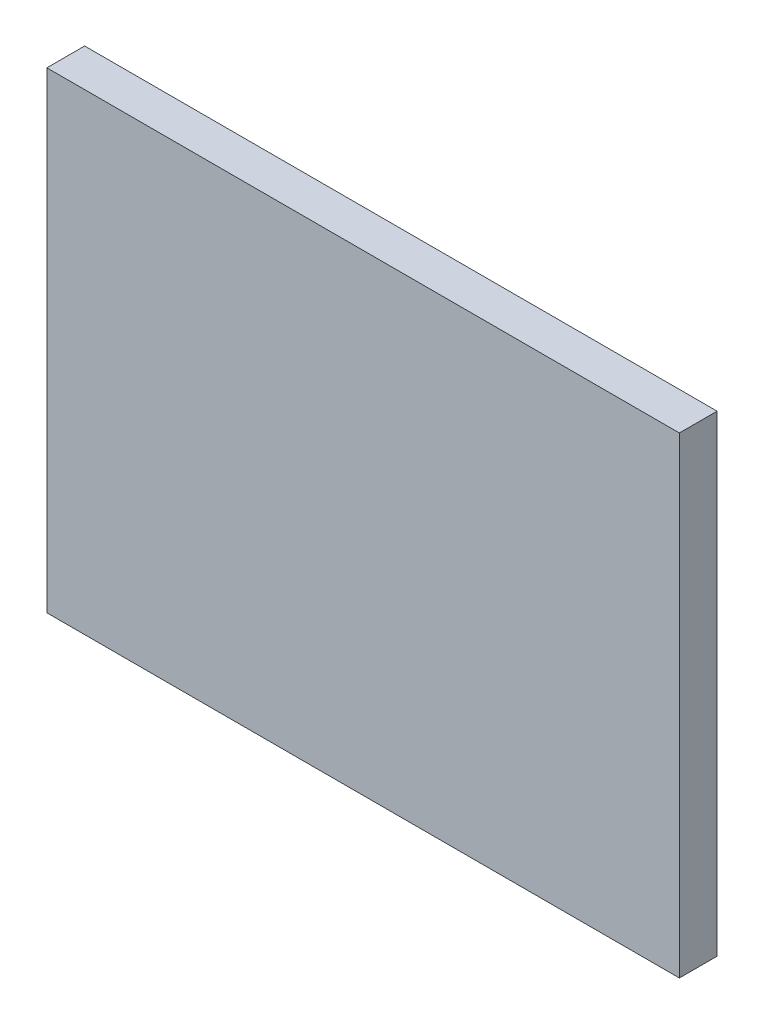
SolidWorks part; units mm, degrees
material "Pine"
ref_plane "Front Plane" through (0, 0, 0) normal (0, 0, 1) x (1, 0, 0)
ref_plane "Top Plane" through (0, 0, 0) normal (0, 1, 0) x (1, 0, 0)
ref_plane "Right Plane" through (0, 0, 0) normal (1, 0, 0) x (0, 0, -1)
sketch "Sketch1" plane through (0, 0, 0) normal (0, 0, 1) x (1, 0, 0)
  line L0 (-5300.6625, 1520.825) -> (-5451.475, 1520.825)
  line L1 (-5456.2375, 1384.3) -> (-5456.2375, 1516.0625)
  line L2 (-5557.8375, 1546.225) -> (-5194.3, 1546.225)
  line L3 (-5557.8375, 1539.875) -> (-5194.3, 1539.875)
  line L4 (-5297.4875, 1377.95) -> (-5454.65, 1377.95)
  line L5 (-5291.1375, 1384.3) -> (-5291.1375, 1516.0625)
  line L6 (-5300.6625, 1525.5875) -> (-5451.475, 1525.5875)
  line L7 (-5461, 1384.3) -> (-5461, 1516.0625)
  line L8 (-5297.4875, 1382.7125) -> (-5454.65, 1382.7125)
  line L9 (-5295.9, 1384.3) -> (-5295.9, 1516.0625)
  line L10 (-5740.4, 998.5375) -> (-5740.4, 1181.1)
  line L11 (-5740.4, 1181.1) -> (-5512.5938, 1181.1)
  line L12 (-5512.5938, 1181.1) -> (-5512.5938, 998.5375)
  line L13 (-5512.5938, 998.5375) -> (-5740.4, 998.5375)
  line L14 (-5258.5938, 1181.1) -> (-5486.4, 1181.1)
  line L15 (-5258.5938, 998.5375) -> (-5258.5938, 1181.1)
  line L16 (-5486.4, 998.5375) -> (-5258.5938, 998.5375)
  line L17 (-5486.4, 1181.1) -> (-5486.4, 998.5375)
  line L18 (-5740.4, 898.525) -> (-5011.7375, 898.525)
  line L19 (-5168.1062, 1384.3) -> (-5168.1062, 1392.2375)
  line L20 (-5176.0437, 1400.175) -> (-5245.8937, 1400.175)
  line L21 (-5253.8313, 1392.2375) -> (-5253.8313, 1384.3)
  line L22 (-5451.475, 1512.8875) -> (-5451.475, 1384.3)
  line L23 (-5303.8375, 1516.0625) -> (-5448.3, 1516.0625)
  line L24 (-5498.3062, 1384.3) -> (-5451.475, 1384.3)
  line L25 (-5253.8313, 1384.3) -> (-5300.6625, 1384.3)
  line L26 (-5584.0312, 1384.3) -> (-5740.4, 1384.3)
  line L27 (-5564.1875, 1536.7) -> (-5740.4, 1536.7)
  line L28 (-5740.4, 1357.3125) -> (-5740.4, 1206.5)
  line L29 (-5011.7375, 1357.3125) -> (-5740.4, 1357.3125)
  line L30 (-5011.7375, 1206.5) -> (-5011.7375, 1357.3125)
  line L31 (-5740.4, 1206.5) -> (-5011.7375, 1206.5)
  line L32 (-4765.675, 1549.4) -> (-4978.4, 1549.4)
  line L33 (-4765.675, 1397) -> (-4765.675, 1549.4)
  line L34 (-4978.4, 1397) -> (-4765.675, 1397)
  line L35 (-4978.4, 1549.4) -> (-4978.4, 1397)
  line L36 (-4765.675, 1371.6) -> (-4978.4, 1371.6)
  line L37 (-4765.675, 1219.2) -> (-4765.675, 1371.6)
  line L38 (-4978.4, 1219.2) -> (-4765.675, 1219.2)
  line L39 (-4978.4, 1371.6) -> (-4978.4, 1219.2)
  line L40 (-5284.7875, 803.275) -> (-5272.0875, 803.275)
  line L41 (-5187.95, 1536.7) -> (-5011.7375, 1536.7)
  line L42 (-5300.6625, 1384.3) -> (-5300.6625, 1512.8875)
  line L43 (-5740.4, 1536.7) -> (-5740.4, 1384.3)
  line L44 (-5557.8375, 1536.7) -> (-5557.8375, 1549.4)
  line L45 (-5557.8375, 1549.4) -> (-5194.3, 1549.4)
  line L46 (-5194.3, 1549.4) -> (-5194.3, 1536.7)
  line L47 (-5011.7375, 1536.7) -> (-5011.7375, 1384.3)
  line L48 (-5011.7375, 1384.3) -> (-5168.1062, 1384.3)
  line L49 (-5498.3062, 1384.3) -> (-5498.3062, 1392.2375)
  line L50 (-5506.2437, 1400.175) -> (-5576.0938, 1400.175)
  line L51 (-5584.0312, 1392.2375) -> (-5584.0312, 1384.3)
  line L52 (-5740.4, 660.4) -> (-5740.4, 898.525)
  line L53 (-5011.7375, 898.525) -> (-5011.7375, 660.4)
  line L54 (-5011.7375, 660.4) -> (-5740.4, 660.4)
  line L55 (-5291.1375, 803.275) -> (-5291.1375, 752.475)
  line L56 (-5265.7375, 752.475) -> (-5265.7375, 803.275)
  line L57 (-5284.7875, 752.475) -> (-5272.0875, 752.475)
  arc A0 (-5451.475, 1520.825) -> (-5456.2375, 1516.0625) centre (-5451.475, 1516.0625) ccw
  arc A1 (-5461, 1384.3) -> (-5454.65, 1377.95) centre (-5454.65, 1384.3) ccw
  arc A2 (-5297.4875, 1377.95) -> (-5291.1375, 1384.3) centre (-5297.4875, 1384.3) ccw
  circle A3 centre (-5037.9312, 1233.4875) radius 1.5875
  circle A4 centre (-5037.9312, 1328.7375) radius 1.5875
  circle A5 centre (-5714.2063, 1233.4875) radius 1.5875
  circle A6 centre (-5714.2063, 1328.7375) radius 1.5875
  circle A7 centre (-5018.0875, 1333.5) radius 1.5875
  circle A8 centre (-5018.0875, 1231.9) radius 1.5875
  circle A9 centre (-5734.05, 1231.9) radius 1.5875
  circle A10 centre (-5734.05, 1333.5) radius 1.5875
  circle A11 centre (-5734.05, 1511.3) radius 1.5875
  circle A12 centre (-5734.05, 1409.7) radius 1.5875
  circle A13 centre (-5018.0875, 1511.3) radius 1.5875
  circle A14 centre (-5018.0875, 1409.7) radius 1.5875
  arc A15 (-5557.8375, 1546.225) -> (-5557.8375, 1539.875) centre (-5557.8375, 1543.05) ccw
  arc A16 (-5194.3, 1539.875) -> (-5194.3, 1546.225) centre (-5194.3, 1543.05) ccw
  arc A17 (-5291.1375, 1516.0625) -> (-5300.6625, 1525.5875) centre (-5300.6625, 1516.0625) ccw
  arc A18 (-5451.475, 1525.5875) -> (-5461, 1516.0625) centre (-5451.475, 1516.0625) ccw
  arc A19 (-5456.2375, 1384.3) -> (-5454.65, 1382.7125) centre (-5454.65, 1384.3) ccw
  arc A20 (-5297.4875, 1382.7125) -> (-5295.9, 1384.3) centre (-5297.4875, 1384.3) ccw
  arc A21 (-5295.9, 1516.0625) -> (-5300.6625, 1520.825) centre (-5300.6625, 1516.0625) ccw
  circle A22 centre (-5702.3, 892.175) radius 1.5875
  circle A23 centre (-5734.05, 860.425) radius 1.5875
  circle A24 centre (-5474.8906, 892.175) radius 1.5875
  circle A25 centre (-5277.2469, 892.175) radius 1.5875
  circle A26 centre (-5049.8375, 892.175) radius 1.5875
  circle A27 centre (-5018.0875, 860.425) radius 1.5875
  circle A28 centre (-5296.6938, 1174.75) radius 1.5875
  circle A29 centre (-5448.3, 1174.75) radius 1.5875
  circle A30 centre (-5264.9437, 1155.7) radius 1.5875
  circle A31 centre (-5264.9437, 1023.9375) radius 1.5875
  circle A32 centre (-5518.9438, 1155.7) radius 1.5875
  circle A33 centre (-5518.9438, 1023.9375) radius 1.5875
  circle A34 centre (-5702.3, 1004.8875) radius 1.5875
  circle A35 centre (-5550.6937, 1004.8875) radius 1.5875
  arc A36 (-5576.0938, 1400.175) -> (-5584.0312, 1392.2375) centre (-5576.0938, 1392.2375) ccw
  arc A37 (-5168.1062, 1392.2375) -> (-5176.0437, 1400.175) centre (-5176.0437, 1392.2375) ccw
  arc A38 (-5245.8937, 1400.175) -> (-5253.8313, 1392.2375) centre (-5245.8937, 1392.2375) ccw
  arc A39 (-5448.3, 1516.0625) -> (-5451.475, 1512.8875) centre (-5448.3, 1512.8875) ccw
  arc A40 (-5284.7875, 803.275) -> (-5291.1375, 803.275) centre (-5287.9625, 803.275) ccw
  circle A41 centre (-5679.2812, 1026.3187) radius 1.5875
  circle A42 centre (-5679.2812, 1153.3187) radius 1.5875
  circle A43 centre (-5571.3313, 1153.3187) radius 1.5875
  circle A44 centre (-5571.3313, 1026.3187) radius 1.5875
  circle A45 centre (-5317.3312, 1153.3187) radius 1.5875
  circle A46 centre (-5317.3312, 1026.3187) radius 1.5875
  circle A47 centre (-5425.2812, 1026.3187) radius 1.5875
  circle A48 centre (-5425.2812, 1153.3187) radius 1.5875
  arc A49 (-5194.3, 1536.7) -> (-5187.95, 1536.7) centre (-5191.125, 1536.7) ccw
  arc A50 (-5564.1875, 1536.7) -> (-5557.8375, 1536.7) centre (-5561.0125, 1536.7) ccw
  arc A51 (-5300.6625, 1512.8875) -> (-5303.8375, 1516.0625) centre (-5303.8375, 1512.8875) ccw
  arc A52 (-5498.3062, 1392.2375) -> (-5506.2437, 1400.175) centre (-5506.2437, 1392.2375) ccw
  circle A53 centre (-5712.46, 784.225) radius 4.7625
  arc A54 (-5272.0875, 752.475) -> (-5265.7375, 752.475) centre (-5268.9125, 752.475) ccw
  arc A55 (-5291.1375, 752.475) -> (-5284.7875, 752.475) centre (-5287.9625, 752.475) ccw
  circle A56 centre (-5182.3938, 684.2125) radius 3.175
  circle A57 centre (-5239.5437, 684.2125) radius 3.175
  circle A58 centre (-5512.5938, 684.2125) radius 3.175
  circle A59 centre (-5569.7437, 684.2125) radius 3.175
  circle A60 centre (-5474.8906, 666.75) radius 1.5875
  circle A61 centre (-5277.2469, 666.75) radius 1.5875
  circle A62 centre (-5734.05, 698.5) radius 1.5875
  circle A63 centre (-5702.3, 666.75) radius 1.5875
  circle A64 centre (-5049.8375, 666.75) radius 1.5875
  circle A65 centre (-5018.0875, 698.5) radius 1.5875
  circle A66 centre (-5713.73, 835.025) radius 4.7625
  circle A67 centre (-5712.46, 819.785) radius 4.7625
  circle A68 centre (-5712.46, 802.005) radius 4.7625
  circle A69 centre (-5714.2063, 1314.45) radius 3.175
  circle A70 centre (-5037.9312, 1314.45) radius 3.175
  arc A71 (-5265.7375, 803.275) -> (-5272.0875, 803.275) centre (-5268.9125, 803.275) ccw
  ellipse E0 centre (-5371.3062, 1089.8188) end of major axis (-5277.6438, 1089.8188) minor radius 65.0875
  ellipse E1 centre (-5625.3062, 1089.8188) end of major axis (-5531.6438, 1089.8188) minor radius 65.0875
sketch "Sketch2" plane through (0, 0, 0) normal (0, 0, 1) x (1, 0, 0)
  line L0 (-4765.675, 1377.95) -> (-4765.675, 1219.2)
  line L1 (-4765.675, 1219.2) -> (-4978.4, 1219.2)
  line L2 (-4978.4, 1219.2) -> (-4978.4, 1377.95)
  line L3 (-4978.4, 1377.95) -> (-4765.675, 1377.95)
  dimension "D1" = 158.75
  dimension "D2" = 212.725
extrude "Extrude1" add sketch "Sketch2" against normal blind 12.7
